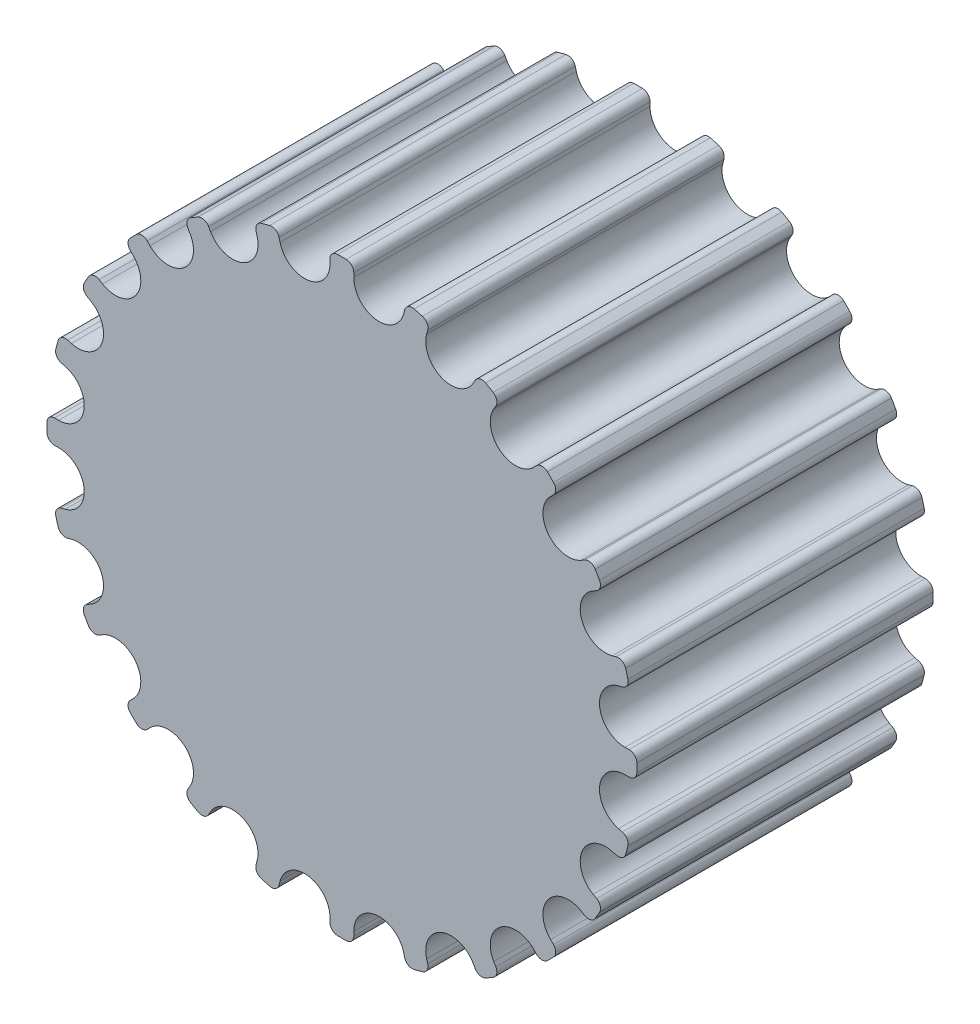
SolidWorks part; units mm, degrees
ref_plane "前视基准面" through (0, 0, 0) normal (0, 0, 1) x (1, 0, 0)
ref_plane "上视基准面" through (0, 0, 0) normal (0, 1, 0) x (1, 0, 0)
ref_plane "右视基准面" through (0, 0, 0) normal (1, 0, 0) x (0, 0, -1)
sketch "Sketch2" plane through (0, 0, 0) normal (0, 0, 1) x (1, 0, 0)
  circle A0 centre (0, 0) radius 29.875
  dimension "D1" = 59.75
extrude "Extrude1" add sketch "Sketch2" along normal blind 30
sketch "Sketch1" plane through (0, 0, 0) normal (0, 0, 1) x (1, 0, 0)
  line L0 (0, 0) -> (0, 30.56) construction
  line L1 (0, 0) -> (-3.9889, 30.2986) construction
  line L2 (-1.2065, 29.0851) -> (-1.203, 28.6801)
  line L3 (-6.3624, 28.4063) -> (-6.261, 28.0142)
  circle A0 centre (0, 0) radius 30.56 construction
  arc A1 (-0.438, 29.8718) -> (-7.3084, 28.9673) centre (0, 0) ccw
  arc A2 (-6.261, 28.0142) -> (-1.203, 28.6801) centre (-3.7729, 28.6577) ccw
  arc A3 (-0.438, 29.8718) -> (-1.2065, 29.0851) centre (-0.4265, 29.0919) ccw
  arc A4 (-7.3084, 28.9673) -> (-6.3624, 28.4063) centre (-7.1175, 28.211) cw
  point P4 (30.2986, 3.9889)
  point P5 (28.2338, 11.6948)
  point P6 (24.2449, 18.6037)
  point P7 (18.6037, 24.2449)
  point P8 (11.6948, 28.2338)
  point P9 (3.9889, 30.2986)
  point P10 (-3.9889, 30.2986)
  point P11 (-11.6948, 28.2338)
  point P12 (-18.6037, 24.2449)
  point P13 (-24.2449, 18.6037)
  point P14 (-28.2338, 11.6948)
  point P15 (-30.2986, 3.9889)
  point P16 (-30.2986, -3.9889)
  point P17 (-28.2338, -11.6948)
  point P18 (-24.2449, -18.6037)
  point P19 (-18.6037, -24.2449)
  point P20 (-11.6948, -28.2338)
  point P21 (-3.9889, -30.2986)
  point P22 (3.9889, -30.2986)
  point P23 (11.6948, -28.2338)
  point P24 (18.6037, -24.2449)
  point P25 (24.2449, -18.6037)
  point P26 (28.2338, -11.6948)
  point P27 (30.2986, -3.9889)
  dimension "D1" = 61.12
  dimension "D2" = 59.75
  dimension "D3" = 5.14
  dimension "D4" = 3.54
  dimension "D5" = 1.56
  dimension "D6" = 7
extrude "Extrude2" cut sketch "Sketch1" along normal up to surface (30 mm away) up to face at (29.875, 0, 30)
pattern_circular "CirPattern1" count 24 over 360 about axis through (0, 0, 0) along (0, 0, 1) of "Extrude2"
